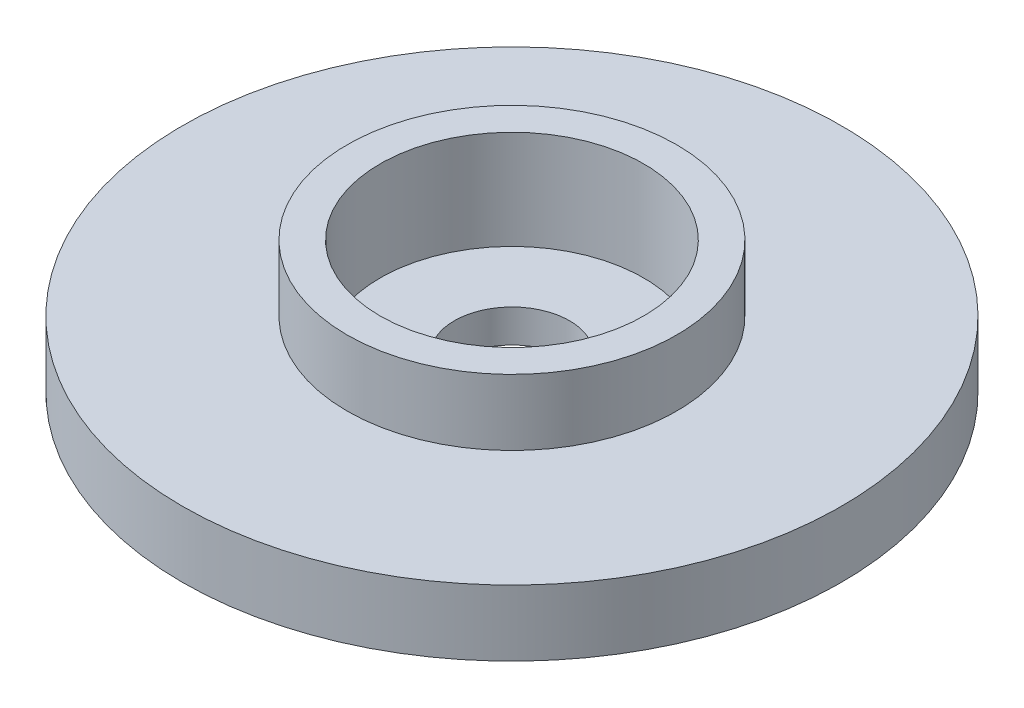
SolidWorks part; units mm, degrees
ref_plane "前视基准面" through (0, 0, 0) normal (0, 0, 1) x (1, 0, 0)
ref_plane "上视基准面" through (0, 0, 0) normal (0, 1, 0) x (1, 0, 0)
ref_plane "右视基准面" through (0, 0, 0) normal (1, 0, 0) x (0, 0, -1)
sketch "草图1" plane through (0, 0, 0) normal (0, 1, 0) x (1, 0, 0)
  circle A0 centre (0, 0) radius 10
  dimension "D2" = 20
extrude "凸台-拉伸1" add sketch "草图1" along normal blind 2
sketch "草图2" plane through (0, 2, 0) normal (0, 1, 0) x (1, 0, 0)
  circle A0 centre (0, 0) radius 5
  dimension "D1" = 10
extrude "凸台-拉伸2" add sketch "草图2" along normal blind 2
sketch "草图3" plane through (0, 4, 0) normal (0, 1, 0) x (1, 0, 0)
  circle A0 centre (0, 0) radius 1.75
  dimension "D1" = 3.5
extrude "切除-拉伸1" cut sketch "草图3" against normal through all
sketch "草图4" plane through (0, 4, 0) normal (0, 1, 0) x (1, 0, 0)
  circle A0 centre (0, 0) radius 4
  dimension "D1" = 8
extrude "切除-拉伸2" cut sketch "草图4" against normal blind 3
scale "缩放比例1" scale about centroid uniform scaling yes scale factor 0.5
